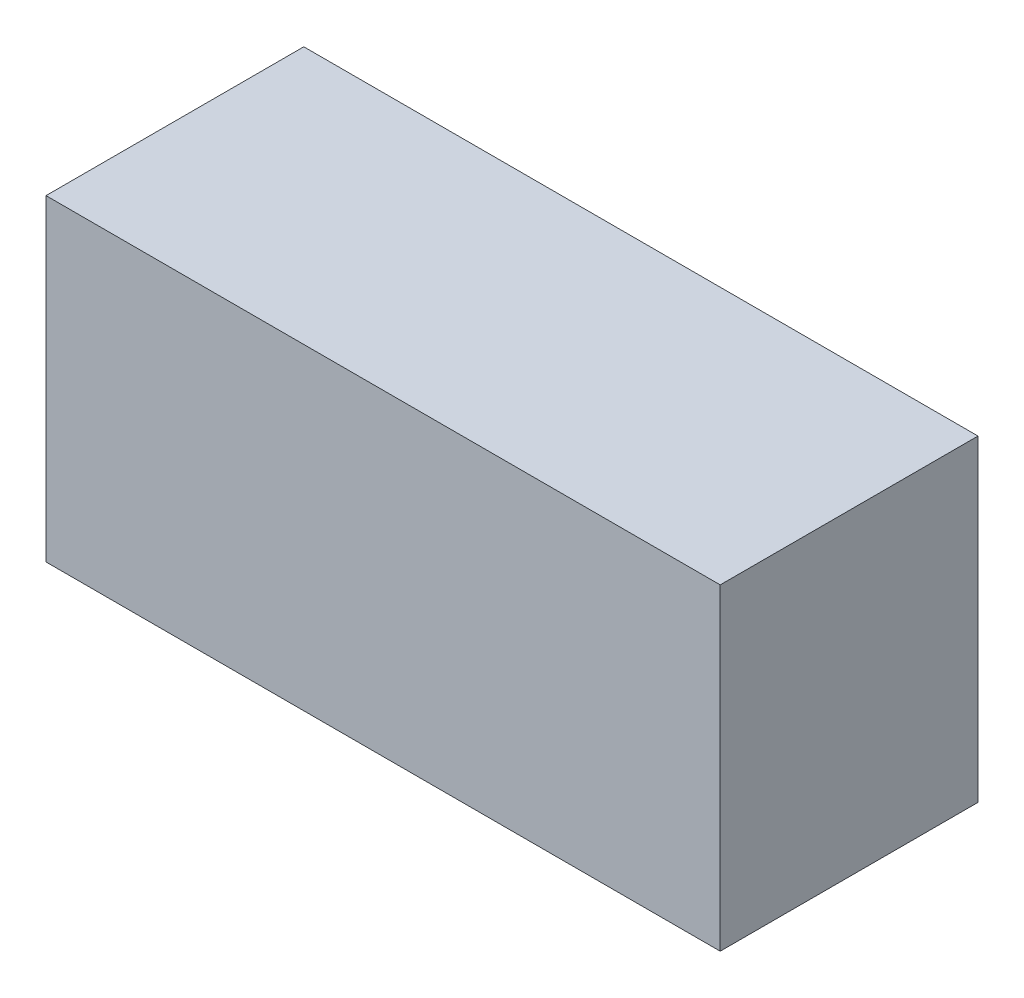
SolidWorks part; units mm, degrees
ref_plane "Front Plane" through (0, 0, 0) normal (0, 0, 1) x (1, 0, 0)
ref_plane "Top Plane" through (0, 0, 0) normal (0, 1, 0) x (1, 0, 0)
ref_plane "Right Plane" through (0, 0, 0) normal (1, 0, 0) x (0, 0, -1)
sketch "Sketch1" plane through (0, 0, 0) normal (0, 0, 1) x (1, 0, 0)
  line L0 (0.175, 0.4) -> (1.875, 0.4)
  line L1 (1.875, 0.4) -> (1.875, -0.4)
  line L2 (1.875, -0.4) -> (0.175, -0.4)
  line L3 (0.175, -0.4) -> (0.175, 0.4)
extrude "Component_Outline" add sketch "Sketch1" along normal blind 0.65 separate body
sketch3d "3DSketch1"
  line L0 (0, 0, 0) -> (1, 0, 0)
  line L1 (0, 0, 0) -> (0, 1, 0)
  line L2 (0, 0, 0) -> (0, 0, 1)
  point P0 (0, 0, 0)
